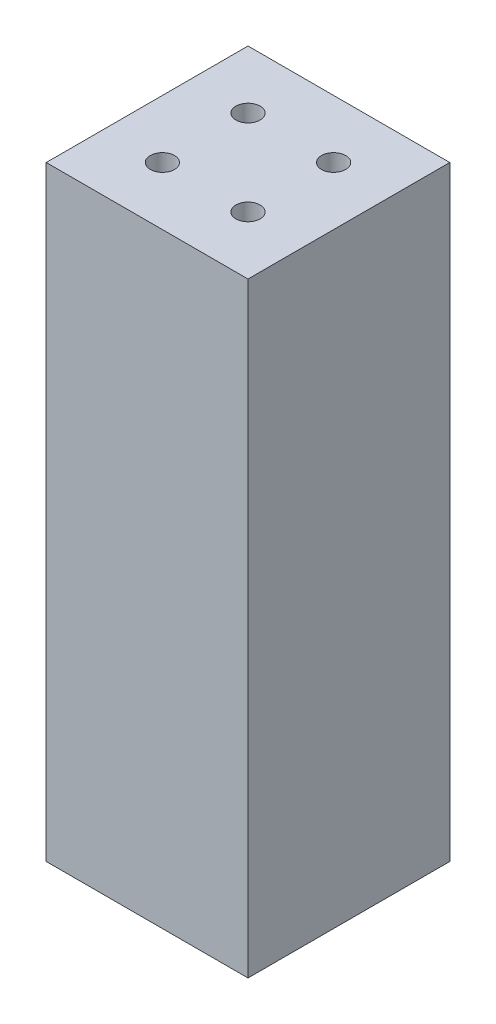
SolidWorks part; units mm, degrees
material "Plain Carbon Steel"
ref_plane "Front Plane" through (0, 0, 0) normal (0, 0, 1) x (1, 0, 0)
ref_plane "Top Plane" through (0, 0, 0) normal (0, 1, 0) x (1, 0, 0)
ref_plane "Right Plane" through (0, 0, 0) normal (1, 0, 0) x (0, 0, -1)
sketch "Sketch1" plane through (0, 0, 0) normal (0, 1, 0) x (1, 0, 0)
  line L1 (12.5, 12.5) -> (-12.5, 12.5)
  line L2 (12.5, 12.5) -> (12.5, -12.5)
  line L3 (12.5, -12.5) -> (-12.5, -12.5)
  line L4 (-12.5, 12.5) -> (-12.5, -12.5)
  line L5 (0, -12.5) -> (0, 12.5) construction
  line L6 (12.5, 0) -> (-12.5, 0) construction
  point P0 (0, 0)
  dimension "D1" = 25
  dimension "D2" = 25
extrude "Boss-Extrude1" add sketch "Sketch1" along normal blind 75
hole_wizard "M3x0.5 Tapped Hole1" positions "Sketch3" profile "Sketch2" tap size "M3x0.5" standard "ANSI Metric"
sketch "Sketch3" plane through (0, 75, 0) normal (0, 1, 0) x (1, 0, 0)
  line L0 (-5.3033, 5.3033) -> (5.3033, -5.3033) construction
  line L3 (5.3033, 5.3033) -> (-5.3033, -5.3033) construction
  line L4 (0, 0) -> (0, -5.4471) construction
  point P0 (-5.3033, -5.3033)
  point P2 (5.3033, -5.3033)
  point P4 (5.3033, 5.3033)
  point P6 (-5.3033, 5.3033)
  dimension "D1" = 15
  dimension "D2" = 45
sketch "Sketch2" plane through (-5.3033, 75, 5.3033) normal (1, 0, 0) x (0, 0, 1)
  line L0 (0, 0) -> (0, 35.9013)
  line L1 (0, 35.9013) -> (1.5, 35)
  line L2 (1.5, 35) -> (1.5, 0)
  line L5 (1.5, 0) -> (0, 0)
  line L10 (0, 35.9013) -> (-1.5, 35) construction
  line L11 (0, -6.35) -> (0, 107.95) construction
  dimension "Tap Drill Dia." = 3
  dimension "Tap Drill Depth" = 35
  dimension "Drill Angle" = 118
cosmetic thread "Hole Thread1"
cosmetic thread "Hole Thread2"
cosmetic thread "Hole Thread3"
cosmetic thread "Hole Thread4"
